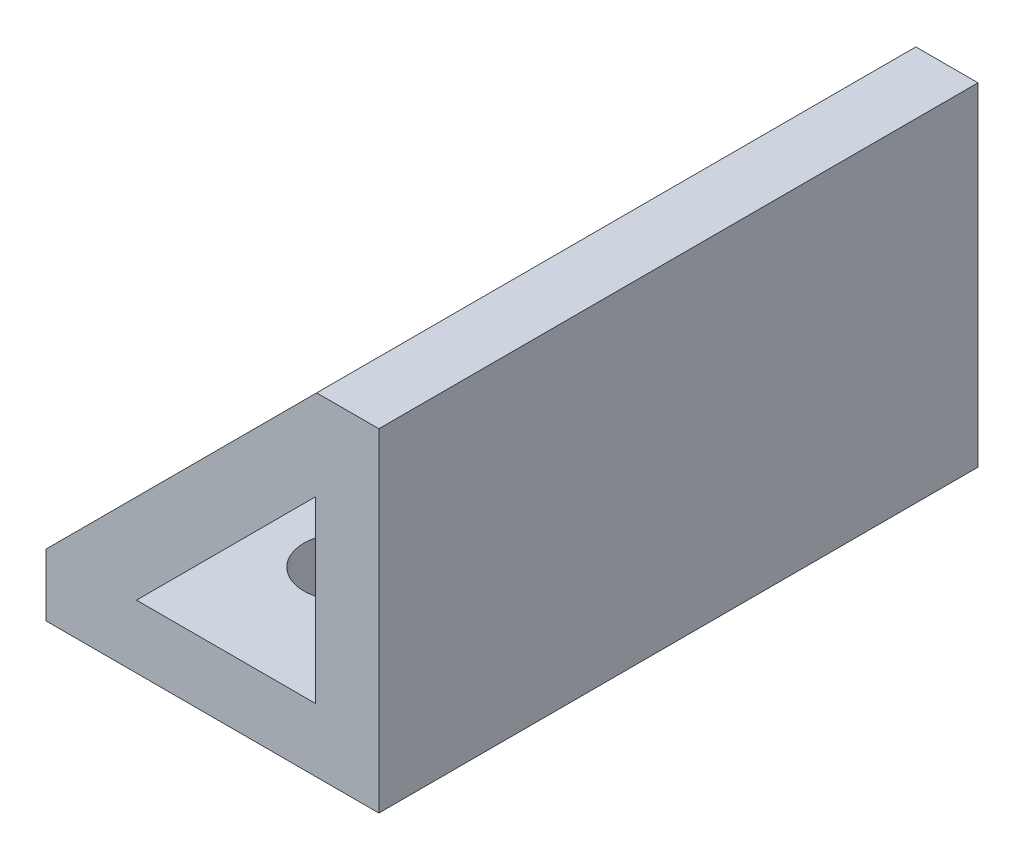
SolidWorks part; units mm, degrees
ref_plane "Front Plane" through (0, 0, 0) normal (0, 0, 1) x (1, 0, 0)
ref_plane "Top Plane" through (0, 0, 0) normal (0, 1, 0) x (1, 0, 0)
ref_plane "Right Plane" through (0, 0, 0) normal (1, 0, 0) x (0, 0, -1)
sketch "Sketch1" plane through (0, 0, 0) normal (0, 0, 1) x (1, 0, 0)
  line L0 (-4.7454, 25.4) -> (-25.4, 4.7454)
  line L1 (-4.7454, 25.4) -> (0, 25.4)
  line L2 (0, 25.4) -> (0, 0)
  line L3 (0, 0) -> (-25.4, 0)
  line L4 (-25.4, 0) -> (-25.4, 4.7454)
  line L5 (-4.826, 18.4944) -> (-4.826, 4.826)
  line L6 (-4.826, 4.826) -> (-18.4944, 4.826)
  line L7 (-18.4944, 4.826) -> (-4.826, 18.4944)
  dimension "D1" = 25.4
  dimension "D2" = 25.4
  dimension "D3" = 29.21
  dimension "D4" = 4.826
  dimension "D5" = 4.826
  dimension "D6" = 4.826
extrude "Boss-Extrude1" add sketch "Sketch1" along normal blind 45.72
sketch "Sketch2" plane through (0, 0, 0) normal (0, -1, 0) x (1, 0, 0)
  line L0 (-25.4, 45.72) -> (0, 45.72) construction
  circle A0 centre (-12.7, 35.56) radius 3.175
  circle A1 centre (-12.7, 10.16) radius 3.175
  point P6 (-12.7, 45.72)
  dimension "D1" = 6.35
  dimension "D2" = 25.4
  dimension "D3" = 10.16
extrude "Cut-Extrude1" cut sketch "Sketch2" against normal through all
sketch "Sketch4" plane through (0, 25.4, 0) normal (0, 1, 0) x (1, 0, 0)
  circle A0 centre (-12.7, -10.16) radius 6.35
  circle A1 centre (-12.7, -35.56) radius 6.35
  dimension "D1" = 12.7
extrude "Cut-Extrude2" cut sketch "Sketch4" against normal blind 19.05
equation "\"D1@Sketch1\"=1"
equation "\"D6@Sketch1\"=\"D4@Sketch1\""
